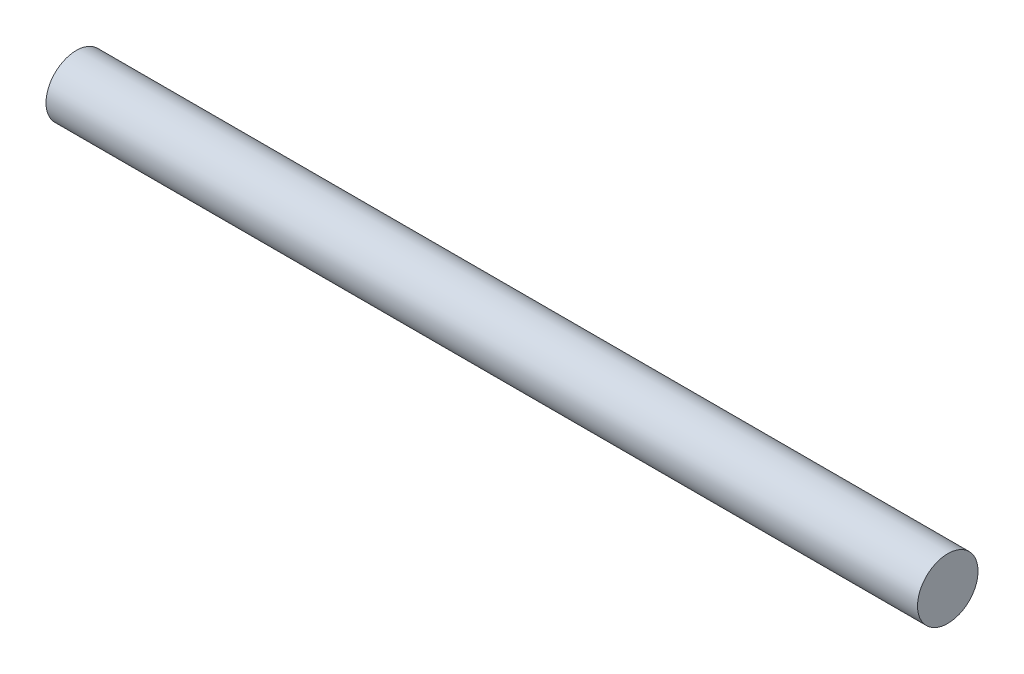
SolidWorks part; units mm, degrees
ref_plane "Спереди" through (0, 0, 0) normal (0, 0, 1) x (1, 0, 0)
ref_plane "Сверху" through (0, 0, 0) normal (0, 1, 0) x (1, 0, 0)
ref_plane "Справа" through (0, 0, 0) normal (1, 0, 0) x (0, 0, -1)
sketch "Эскиз1" plane through (0, 0, 0) normal (1, 0, 0) x (0, 0, -1)
  circle A0 centre (0, 0) radius 25
  dimension "D1" = 50
extrude "Бобышка-Вытянуть1" add sketch "Эскиз1" along normal blind 720
